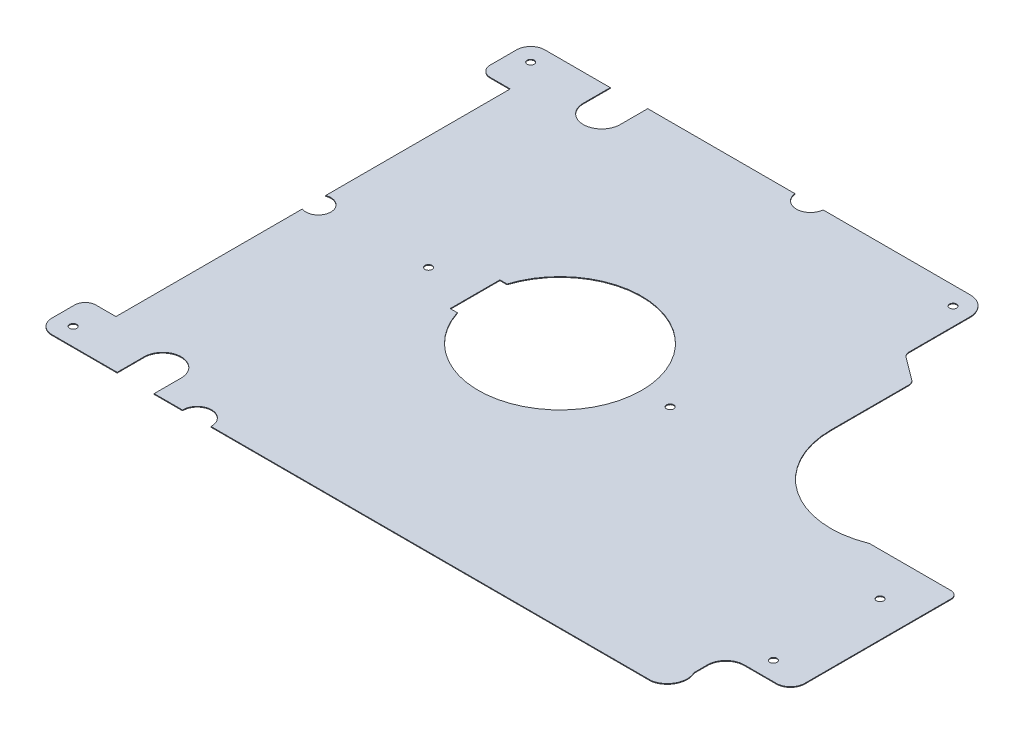
SolidWorks part; units mm, degrees
ref_plane "Alzado" through (0, 0, 0) normal (0, 0, 1) x (1, 0, 0)
ref_plane "Planta" through (0, 0, 0) normal (0, 1, 0) x (1, 0, 0)
ref_plane "Vista lateral" through (0, 0, 0) normal (1, 0, 0) x (0, 0, -1)
sketch "Croquis1" plane through (0, 0, 0) normal (0, 1, 0) x (1, 0, 0)
  line L0 (-33.4, 34.7744) -> (-12.6817, 34.7744)
  line L1 (-38.6, 30.9) -> (-38.6, 34.7)
  line L2 (-8.7047, 34.7744) -> (11.8041, 34.7744)
  line L3 (-38.6, 34.7) -> (-47.8, 34.7)
  line L4 (45.7, -26.2256) -> (41.2, -26.2256)
  line L5 (-49.8, 32.7) -> (-49.8, 29)
  line L6 (-25.4014, -34.7) -> (36.6051, -34.7)
  line L7 (-48.3, 27.5) -> (-45.4787, 27.5)
  line L8 (-45.4787, 27.5) -> (-45.4787, 1.5244)
  line L9 (-45.4787, -28) -> (-48.3, -28)
  line L10 (-45.4787, -1.7756) -> (-45.4787, -28)
  line L11 (-49.8, -29.5) -> (-49.8, -32.7)
  line L13 (-47.8, -34.7) -> (-38.6, -34.7)
  line L15 (-38.6, -30.9) -> (-38.6, -34.7)
  line L20 (18.6549, 8.4803) -> (18.6549, 19.4803)
  line L21 (18.2549, 20.2803) -> (15.0549, 22.6803)
  line L22 (14.6549, 23.4803) -> (14.6549, 32.0967)
  line L27 (47.7, -24.2256) -> (47.7, -3.6256)
  line L28 (46.7, -2.6256) -> (35.3926, -2.6256)
  line L33 (-33.4, 34.7744) -> (-33.4, 30.9)
  line L35 (-33.4, -30.9) -> (-33.4, -34.7)
  line L36 (-33.4, -34.7) -> (-29.3986, -34.7)
  line L37 (38.6, -30.7256) -> (38.6, -28.8256)
  arc A0 (14.6549, 32.0967) -> (11.8041, 34.7744) centre (11.9719, 32.0967) ccw
  arc A1 (-38.6, 30.9) -> (-33.4, 30.9) centre (-36, 30.9) ccw
  arc A2 (45.7, -26.2256) -> (47.7, -24.2256) centre (45.7, -24.2256) ccw
  arc A3 (-47.8, 34.7) -> (-49.8, 32.7) centre (-47.8, 32.7) ccw
  arc A4 (-12.6817, 34.7744) -> (-8.7047, 34.7744) centre (-10.6932, 34.9883) ccw
  arc A5 (-49.8, -32.7) -> (-47.8, -34.7) centre (-47.8, -32.7) ccw
  arc A6 (-29.3986, -34.7) -> (-25.4014, -34.7) centre (-27.4, -34.6256) cw
  arc A7 (-33.4, -30.9) -> (-38.6, -30.9) centre (-36, -30.9) ccw
  arc A8 (36.6051, -34.7) -> (38.6, -30.7256) centre (36.0822, -31.9497) ccw
  arc A9 (-49.8, 29) -> (-48.3, 27.5) centre (-48.3, 29) ccw
  arc A10 (-48.3, -28) -> (-49.8, -29.5) centre (-48.3, -29.5) ccw
  arc A11 (-45.4787, 1.5244) -> (-45.4787, -1.7756) centre (-44.8616, -0.1256) cw
  arc A15 (14.6549, 23.4803) -> (15.0549, 22.6803) centre (15.6549, 23.4803) ccw
  arc A16 (18.6549, 19.4803) -> (18.2549, 20.2803) centre (17.6549, 19.4803) ccw
  arc A17 (18.6549, 8.4803) -> (35.0282, -2.6944) centre (30.6549, 8.4803) ccw
  arc A19 (35.3926, -2.6256) -> (35.0282, -2.6944) centre (35.3926, -3.6256) ccw
  arc A22 (47.7, -3.6256) -> (46.7, -2.6256) centre (46.7, -3.6256) ccw
  arc A29 (41.2, -26.2256) -> (38.6, -28.8256) centre (41.2, -28.8256) ccw
  point P24 (14.6549, 34.7)
  point P33 (47.7, -26.3)
  point P54 (38.6, -34.7)
  dimension "D6" = 1.5
  dimension "D7" = 2
  dimension "D8" = 1
  dimension "D9" = 2.7996
  dimension "D4" = 2
  dimension "D22" = 25.4014
  dimension "D24" = 8.4803
  dimension "D3" = 2
  dimension "D5" = 2
  dimension "D1" = 2.683
  dimension "D10" = 11.8041
  dimension "D11" = 11.9719
  dimension "D12" = 2.6
  dimension "D13" = 1
  dimension "D14" = 1
  dimension "D15" = 12
  dimension "D16" = 15.0549
  dimension "D17" = 17.6549
  dimension "D18" = 2.6
  dimension "D32" = 36
  dimension "D34" = 1.7616
  dimension "D19" = 35.0282
  dimension "D20" = 8.7047
  dimension "D21" = 10.6932
  dimension "D23" = 27.4
  dimension "D25" = 19.4803
  dimension "D26" = 36.0822
  dimension "D27" = 36.6051
  dimension "D28" = 38.6
  dimension "D29" = 47.7
  dimension "D30" = 32.0967
  dimension "D31" = 30.7256
  dimension "D33" = 27.5
  dimension "D35" = 30.9
  dimension "D36" = 30.9
  dimension "D37" = 45.4787
  dimension "D38" = 49.8
  dimension "D39" = 34.7
  dimension "D40" = 44.8616
  dimension "D41" = 1.5244
  dimension "D44" = 26.2256
  dimension "D45" = 26.3
  dimension "D46" = 28
extrude "Extruir1" add sketch "Croquis1" along normal blind 0.1
sketch "Croquis2" plane through (0, 0.1, 0) normal (0, 1, 0) x (1, 0, 0)
  line L0 (-38.6, 34.7) -> (-47.8, 34.7) construction
  line L1 (-49.8, 32.7) -> (-49.8, 29) construction
  line L2 (-45.4787, 27.5) -> (-45.4787, 1.5244) construction
  line L4 (-22.9332, 3.5) -> (-21.9332, 3.5)
  line L5 (-22.9332, 3.5) -> (-22.9332, -3.5)
  line L6 (-22.9332, -3.5) -> (-21.9332, -3.5)
  line L7 (-47.8, -34.7) -> (-38.6, -34.7) construction
  line L8 (46.7, -2.6256) -> (35.3926, -2.6256) construction
  line L9 (47.7, -24.2256) -> (47.7, -3.6256) construction
  line L10 (14.6549, 23.4803) -> (14.6549, 32.0967) construction
  arc A0 (-21.9332, -3.5) -> (-21.9332, 3.5) centre (-10.9787, 0) ccw
  circle A1 centre (-29.4787, 0) radius 0.5
  circle A2 centre (-47.3, 32.2) radius 0.5
  circle A3 centre (-47.3, -32.2) radius 0.5
  circle A4 centre (12.1549, 32.2) radius 0.5
  circle A5 centre (4.5213, 0) radius 0.5
  circle A6 centre (42.7, -8.6256) radius 0.5
  circle A7 centre (42.7, -23.6256) radius 0.5
  point P5 (-22.4787, 0)
  dimension "D1" = 23
  dimension "D2" = 23
  dimension "D5" = 1
  dimension "D6" = 1
  dimension "D7" = 1
  dimension "D8" = 1
  dimension "D9" = 1
  dimension "D10" = 1
  dimension "D11" = 1
  dimension "D3" = 7
  dimension "D4" = 1
  dimension "D12" = 34
  dimension "D13" = 16
  dimension "D14" = 2.5
  dimension "D15" = 2.5
  dimension "D16" = 2.5
  dimension "D17" = 2.5
  dimension "D18" = 15
  dimension "D19" = 6
  dimension "D20" = 5
extrude "Extruir2" cut sketch "Croquis2" against normal through all
